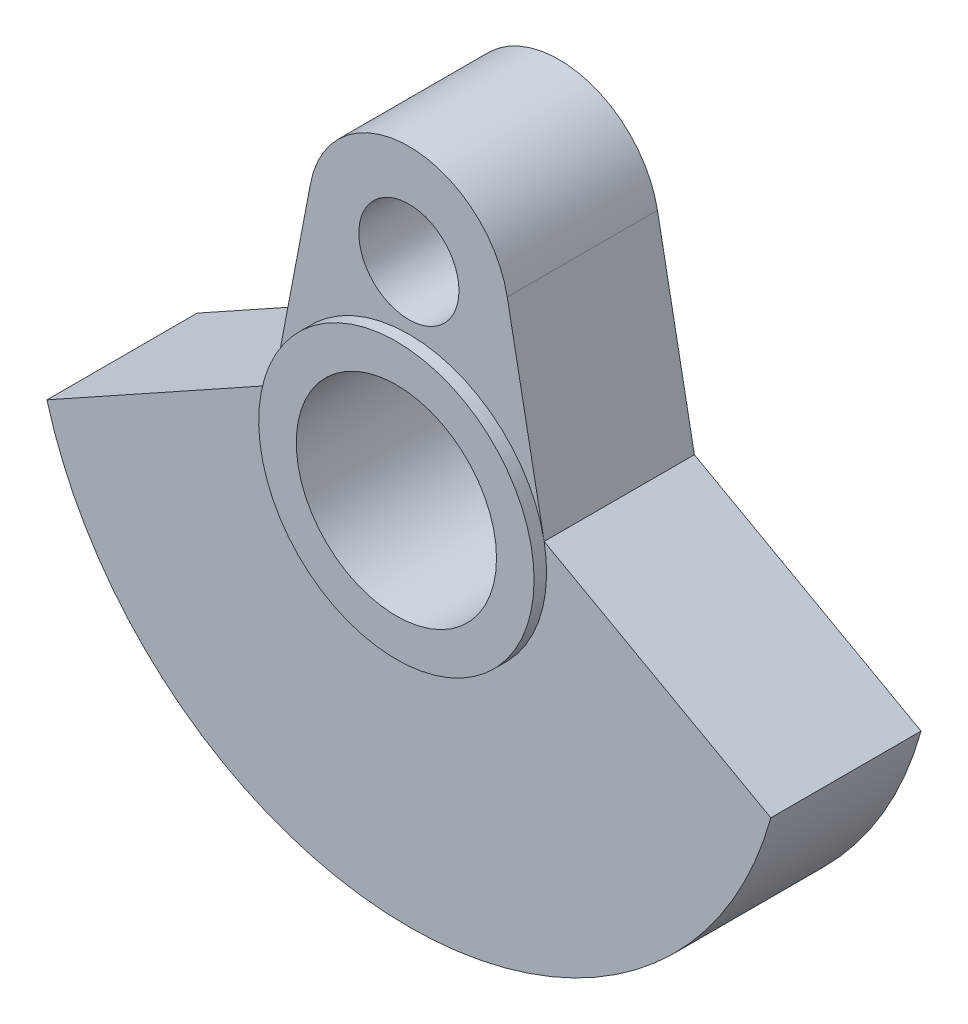
SolidWorks part; units mm, degrees
ref_plane "Front Plane" through (0, 0, 0) normal (0, 0, 1) x (1, 0, 0)
ref_plane "Top Plane" through (0, 0, 0) normal (0, 1, 0) x (1, 0, 0)
ref_plane "Right Plane" through (0, 0, 0) normal (1, 0, 0) x (0, 0, -1)
sketch "Sketch1" plane through (0, 0, 0) normal (0, 0, 1) x (1, 0, 0)
  line L1 (-5.4025, -6.9688) -> (-3.9291, 0.75)
  line L2 (5.4025, -6.9688) -> (3.9291, 0.75)
  line L3 (-5.4025, -6.9688) -> (-14.4568, -12)
  line L4 (5.4025, -6.9688) -> (14.4568, -12)
  circle A0 centre (0, 0) radius 2
  circle A1 centre (0, -8) radius 4
  arc A2 (3.9291, 0.75) -> (-3.9291, 0.75) centre (0, 0) ccw
  arc A3 (-14.4568, -12) -> (14.4568, -12) centre (0, -8) ccw
  dimension "D1" = 4
  dimension "D2" = 8
  dimension "D4" = 8
  dimension "D5" = 30
  dimension "D6" = 3.9291
  dimension "D3" = 8
  dimension "D7" = 4
  dimension "D8" = 5.4025
  dimension "D9" = 3.9291
extrude "Boss-Extrude1" add sketch "Sketch1" along normal blind 6
sketch "Sketch2" plane through (0, 0, 6) normal (0, 0, 1) x (1, 0, 0)
  circle A0 centre (0, -8) radius 5.5
  dimension "D1" = 11
extrude "Boss-Extrude2" add sketch "Sketch2" along normal blind 0.5
sketch "Sketch3" plane through (0, 0, 6.5) normal (0, 0, 1) x (1, 0, 0)
  circle A0 centre (0, -8) radius 4
  dimension "D1" = 8
extrude "Cut-Extrude1" cut sketch "Sketch3" against normal blind 10.5
ref_plane "Plane1" through (0, -23, 0) normal (0, 1, 0) x (1, 0, 0)
